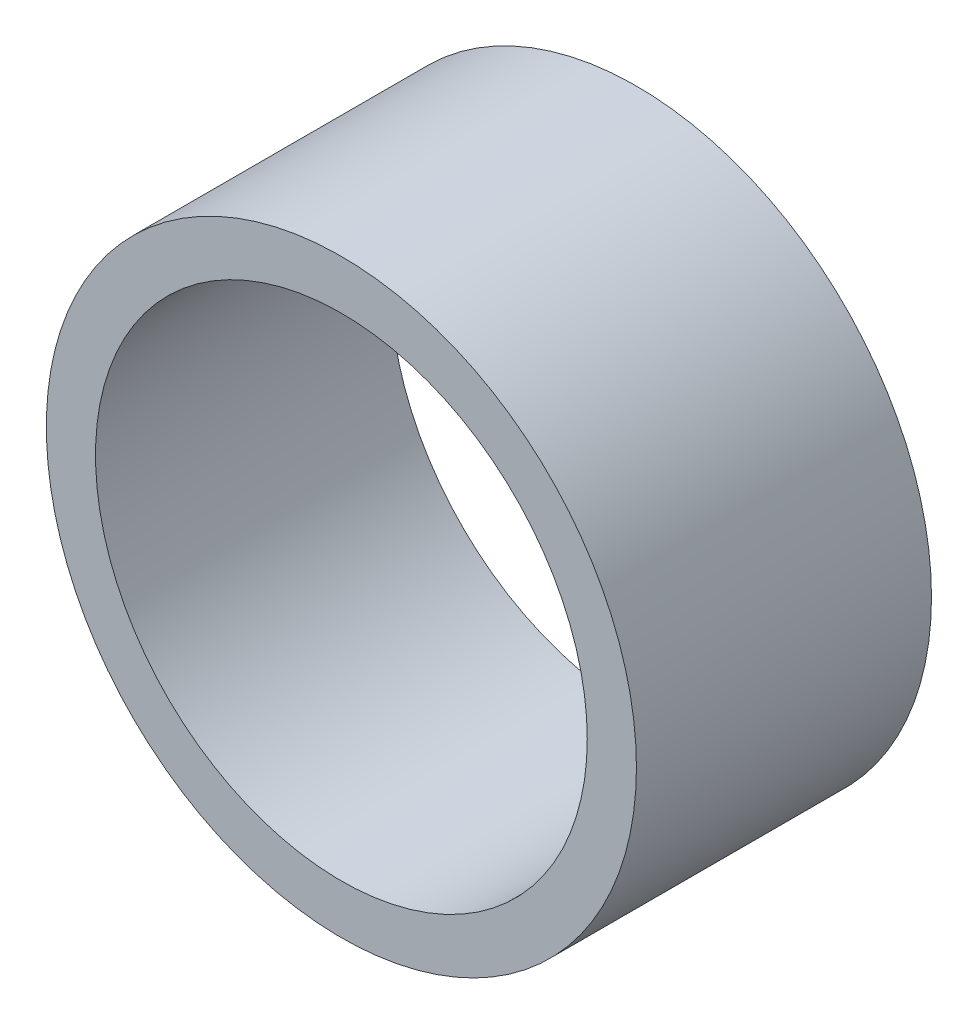
SolidWorks part; units mm, degrees
material "6061 合金"
ref_plane "前视基准面" through (0, 0, 0) normal (0, 0, 1) x (1, 0, 0)
ref_plane "上视基准面" through (0, 0, 0) normal (0, 1, 0) x (1, 0, 0)
ref_plane "右视基准面" through (0, 0, 0) normal (1, 0, 0) x (0, 0, -1)
other "Configuration Table"
sketch "草图1" plane through (0, 0, 0) normal (0, 0, 1) x (1, 0, 0)
  circle A0 centre (0, 0) radius 5
  circle A1 centre (0, 0) radius 6
  dimension "D1" = 10
  dimension "D2" = 12
extrude "凸台-拉伸1" add sketch "草图1" along normal blind 6 contours A0 | A1
sketch "草图2" plane through (0, 0, 0) normal (0, 0, -1) x (-1, 0, 0)
  circle A0 centre (0, 0) radius 7
  circle A1 centre (0, 0) radius 5 construction
  circle A2 centre (0, 0) radius 5
  dimension "D1" = 14
extrude "凸台-拉伸2" [suppressed] add sketch "草图2" against normal blind 1
sketch "草图3" [suppressed] plane through (0, 0, 15) normal (0, 0, 1) x (1, 0, 0)
  circle A1 centre (0, 0) radius 5 construction
  circle A2 centre (0, 0) radius 5
  circle A3 centre (0, 0) radius 7 construction
  circle A4 centre (0, 0) radius 7
extrude "凸台-拉伸3" [suppressed] add sketch "草图3" against normal blind 1
fillet "圆角1" [suppressed] radius 0.5
chamfer "倒角1" [suppressed] distance 0.5 angle 45
